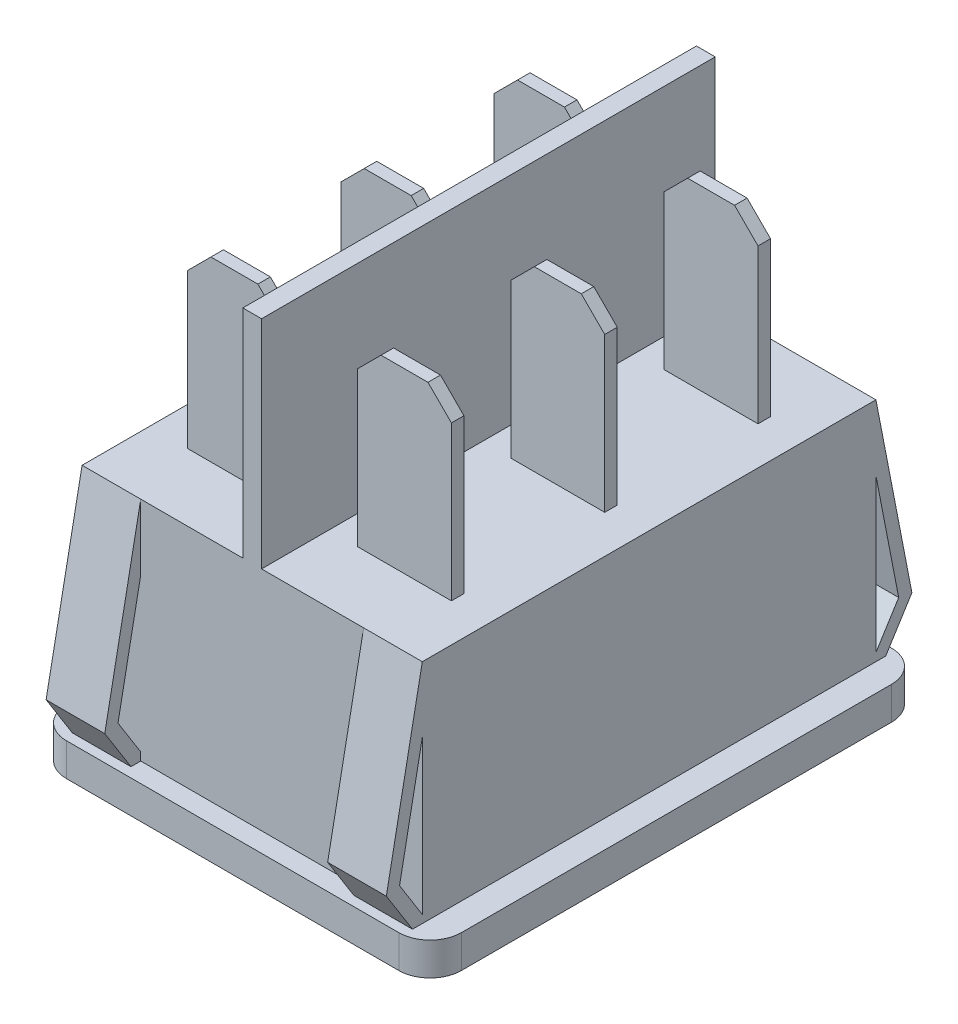
SolidWorks part; units mm, degrees
ref_plane "Front Plane" through (0, 0, 0) normal (0, 0, 1) x (1, 0, 0)
ref_plane "Top Plane" through (0, 0, 0) normal (0, 1, 0) x (1, 0, 0)
ref_plane "Right Plane" through (0, 0, 0) normal (1, 0, 0) x (0, 0, -1)
sketch "Sketch1" plane through (0, 0, 0) normal (0, 1, 0) x (1, 0, 0)
  line L1 (-10.875, -14.5) -> (10.875, -14.5)
  line L2 (-10.875, -14.5) -> (-10.875, 14.5)
  line L3 (-10.875, 14.5) -> (10.875, 14.5)
  line L4 (10.875, -14.5) -> (10.875, 14.5)
  line L5 (-10.875, -14.5) -> (10.875, 14.5) construction
  line L6 (-10.875, 14.5) -> (10.875, -14.5) construction
  point P0 (0, 0)
  dimension "D1" = 21.75
  dimension "D2" = 29
extrude "Boss-Extrude1" add sketch "Sketch1" along normal blind 16.6
sketch "Sketch2" plane through (0, 0, 0) normal (0, 1, 0) x (1, 0, 0)
  line L1 (-12.625, 15.75) -> (12.625, 15.75)
  line L2 (-12.625, 15.75) -> (-12.625, -15.75)
  line L3 (-12.625, -15.75) -> (12.625, -15.75)
  line L4 (12.625, 15.75) -> (12.625, -15.75)
  line L5 (-12.625, 15.75) -> (12.625, -15.75) construction
  line L6 (-12.625, -15.75) -> (12.625, 15.75) construction
  point P0 (0, 0)
  dimension "D1" = 31.5
  dimension "D2" = 25.25
extrude "Boss-Extrude2" add sketch "Sketch2" along normal blind 2.1
sketch "Sketch3" plane through (0, 16.6, 0) normal (0, 1, 0) x (1, 0, 0)
  line L0 (0, -14.5) -> (0, 14.5) construction
  line L1 (10.875, 14.5) -> (-10.875, 14.5) construction
  line L2 (0.6, -14.5) -> (0.6, 14.5)
  line L3 (-0.6, -14.5) -> (-0.6, 14.5)
  line L4 (-0.6, 14.5) -> (0.6, 14.5)
  line L5 (-0.6, -14.5) -> (0.6, -14.5)
  point P6 (0, 0)
  dimension "D1" = 0.6
  dimension "D2" = 0.6
extrude "Boss-Extrude3" add sketch "Sketch3" along normal blind 13.85
sketch "Sketch4" plane through (12.625, 0, 0) normal (1, 0, 0) x (0, 0, -1)
  line L0 (0, 0) -> (0, -12.686) construction
  line L1 (-15.75, 0) -> (15.75, 0) construction
  line L2 (-12.25, 0) -> (-11.339, -3.4)
  line L3 (-15.75, 2.1) -> (-15.75, 0) construction
  line L4 (-12.25, 0) -> (-12.25, -4.5975) construction
  line L5 (-12.25, 0) -> (12.25, 0)
  line L6 (12.25, 0) -> (11.339, -3.4)
  arc A0 (11.339, -3.4) -> (-11.339, -3.4) centre (0, -38.2145) ccw
  dimension "D2" = 36.6145
  dimension "D1" = 3.5
  dimension "D3" = 3.4
  dimension "D4" = 15
extrude "Boss-Extrude4" add sketch "Sketch4" against normal blind 18.3 from offset 3.65 offset against normal yes
sketch "Sketch5" plane through (0, 16.6, 0) normal (0, 1, 0) x (1, 0, 0)
  line L0 (0, 0) -> (10.875, 0) construction
  line L1 (10.875, -14.5) -> (10.875, 14.5) construction
  line L2 (5.4375, -14.5) -> (5.4375, 14.5) construction
  line L3 (10.875, 14.5) -> (-10.875, 14.5) construction
  line L4 (2.4375, 9.4) -> (2.4375, 10.2)
  line L5 (2.4375, -0.4) -> (8.4375, -0.4)
  line L6 (2.4375, -0.4) -> (2.4375, 0.4)
  line L7 (2.4375, 0.4) -> (8.4375, 0.4)
  line L8 (8.4375, -0.4) -> (8.4375, 0.4)
  line L9 (2.4375, -0.4) -> (8.4375, 0.4) construction
  line L10 (2.4375, 0.4) -> (8.4375, -0.4) construction
  line L11 (2.4375, 9.4) -> (8.4375, 9.4)
  line L12 (8.4375, 9.4) -> (8.4375, 10.2)
  line L13 (2.4375, 10.2) -> (8.4375, 10.2)
  line L14 (2.4375, -10.2) -> (2.4375, -9.4)
  line L15 (2.4375, -10.2) -> (8.4375, -10.2)
  line L16 (8.4375, -10.2) -> (8.4375, -9.4)
  line L17 (2.4375, -9.4) -> (8.4375, -9.4)
  line L18 (0, 0) -> (0, 14.5) construction
  line L19 (-2.4375, -10.2) -> (-8.4375, -10.2)
  line L20 (-8.4375, -10.2) -> (-8.4375, -9.4)
  line L21 (-2.4375, -9.4) -> (-8.4375, -9.4)
  line L22 (-2.4375, -10.2) -> (-2.4375, -9.4)
  line L23 (-2.4375, 0.4) -> (-8.4375, 0.4)
  line L24 (-8.4375, -0.4) -> (-8.4375, 0.4)
  line L25 (-2.4375, -0.4) -> (-8.4375, -0.4)
  line L26 (-2.4375, -0.4) -> (-2.4375, 0.4)
  line L27 (-2.4375, 9.4) -> (-8.4375, 9.4)
  line L28 (-8.4375, 9.4) -> (-8.4375, 10.2)
  line L29 (-2.4375, 10.2) -> (-8.4375, 10.2)
  line L30 (-2.4375, 9.4) -> (-2.4375, 10.2)
  point P5 (5.4375, 0)
  point P10 (5.4375, 0)
  dimension "D1" = 0.8
  dimension "D2" = 6
  dimension "D5" = 9
  dimension "D6" = 9
  dimension "D3" = 2
  dimension "D4" = 2
extrude "Boss-Extrude6" add sketch "Sketch5" along normal blind 11.35
chamfer "Chamfer2" distance 1.5 angle 45 12 edges at (-8.4375, 27.95, -9.8) (-2.4375, 27.95, -9.8) (-2.4375, 27.95, 0) (-8.4375, 27.95, 0) (-8.4375, 27.95, 9.8) (-2.4375, 27.95, 9.8) (8.4375, 27.95, 9.8) (2.4375, 27.95, 9.8) (8.4375, 27.95, -9.8) (2.4375, 27.95, -9.8) (2.4375, 27.95, 0) (8.4375, 27.95, 0)
fillet "Fillet1" radius 2 4 edges at (12.625, 1.05, -15.75) (12.625, 1.05, 15.75) (-12.625, 1.05, 15.75) (-12.625, 1.05, -15.75)
fillet "Fillet2" radius 1.5 2 edges at (-0.175, -3.4, 11.339) (-0.175, -3.4, -11.339)
sketch "Sketch6" plane through (-10.875, 0, 0) normal (-1, 0, 0) x (0, 0, 1)
  line L0 (-15.75, 2.1) -> (-14.5, 2.1) construction
  line L1 (-14.5, 2.1) -> (-14.5, 16.6) construction
  line L2 (-14.5, 16.6) -> (-14.5, 2.1) construction
  line L3 (-14.5, 16.6) -> (-16.8, 4.7675)
  line L4 (-16.8, 4.7675) -> (-15.125, 2.1)
  line L5 (-14.5, 12.4073) -> (-15.9544, 4.9252)
  line L6 (-15.9544, 4.9252) -> (-14.5, 2.609)
  line L7 (-15.125, 2.1) -> (-14.5, 2.1)
  line L8 (-14.5, 2.1) -> (-14.5, 2.609)
  line L9 (-15.9544, 4.9252) -> (-14.4475, 2.5254) construction
  line L10 (-14.5, 16.6) -> (-14.5, 12.4073)
  line L11 (-13.7147, 16.4474) -> (-15.9544, 4.9252) construction
  dimension "D1" = 2.3
  dimension "D2" = 11
  dimension "D3" = 0.8
extrude "Boss-Extrude7" add sketch "Sketch6" against normal blind 3.75
mirror "Mirror1" about plane through (0, 0, 0) normal (1, 0, 0) of "Boss-Extrude7"
mirror "Mirror2" about plane through (0, 0, 0) normal (0, 0, 1) of "Mirror1", "Boss-Extrude7"
